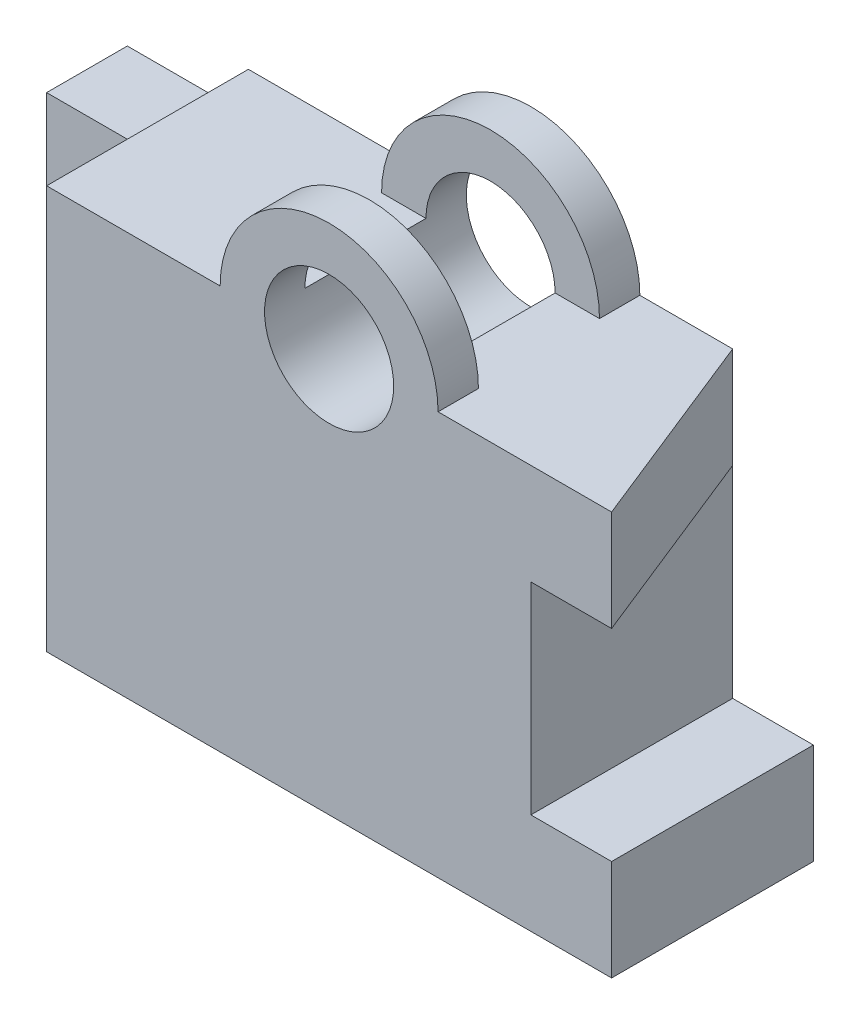
SolidWorks part; units mm, degrees
ref_plane "Спереди" through (0, 0, 0) normal (0, 0, 1) x (1, 0, 0)
ref_plane "Сверху" through (0, 0, 0) normal (0, 1, 0) x (1, 0, 0)
ref_plane "Справа" through (0, 0, 0) normal (1, 0, 0) x (0, 0, -1)
sketch "Эскиз1" plane through (0, 0, 0) normal (0, 0, 1) x (1, 0, 0)
  line L1 (-35, -25) -> (35, -25)
  line L2 (-35, -25) -> (-35, 25)
  line L3 (-35, 25) -> (35, 25)
  line L4 (35, -25) -> (35, 25)
  line L5 (-35, -25) -> (35, 25) construction
  line L6 (-35, 25) -> (35, -25) construction
  line L7 (25, -12.5) -> (35, -12.5)
  line L8 (25, -12.5) -> (25, 12.5)
  line L9 (25, 12.5) -> (35, 12.5)
  line L10 (35, -12.5) -> (35, 12.5)
  line L11 (25, -12.5) -> (35, 12.5) construction
  line L12 (25, 12.5) -> (35, -12.5) construction
  line L13 (-4, -19) -> (4, -19)
  line L14 (-4, -19) -> (-4, -4)
  line L15 (-4, -4) -> (4, -4)
  line L16 (4, -19) -> (4, -4)
  line L17 (-4, -19) -> (4, -4) construction
  line L18 (-4, -4) -> (4, -19) construction
  line L19 (-4, -4) -> (0, -4)
  line L20 (-4, -4) -> (-4, 4)
  line L21 (-4, 4) -> (0, 4)
  line L22 (0, -4) -> (0, 4)
  circle A0 centre (0, 25) radius 8
  point P0 (0, 0)
  point P6 (30, 0)
  point P13 (0, -11.5)
  dimension "D5" = 16
  dimension "D1" = 70
  dimension "D2" = 50
  dimension "D3" = 10
  dimension "D4" = 25
  dimension "D6" = 6
  dimension "D7" = 8
  dimension "D8" = 15
  dimension "D9" = 8
extrude "Бобышка-Вытянуть1" add sketch "Эскиз1" along normal blind 25 contours A0 L3 L2 L1 L4 L7 L8 L9 L22 L15 L16 L13 L14 L20 L21
sketch "Эскиз3" plane through (0, 0, 25) normal (0, 0, 1) x (1, 0, 0)
  circle A0 centre (0, 25) radius 13.5
  circle A1 centre (0, 25) radius 8
  arc A2 (-8, 25) -> (8, 25) centre (0, 25) ccw construction
  dimension "D1" = 27
extrude "Бобышка-Вытянуть2" add sketch "Эскиз3" against normal blind 5
sketch "Эскиз4" plane through (0, 12.5, 0) normal (0, -1, 0) x (1, 0, 0)
  line L0 (35, 25) -> (25, 0)
  line L1 (25, 0) -> (35, 0)
  line L2 (35, 0) -> (35, 25)
extrude "Вырез-Вытянуть1" cut sketch "Эскиз4" against normal through all
sketch "Эскиз5" plane through (0, 0, 25) normal (0, 0, 1) x (1, 0, 0)
  line L0 (-35, 0) -> (25, 0) construction
  line L1 (-35, -25) -> (-35, 25) construction
  line L2 (25, -12.5) -> (25, 12.5) construction
  line L4 (-25, -7) -> (-35, -7)
  line L5 (-25, -7) -> (-25, 7)
  line L6 (-25, 7) -> (-35, 7)
  line L7 (-35, -7) -> (-35, 7)
  line L8 (-25, -7) -> (-35, 7) construction
  line L9 (-25, 7) -> (-35, -7) construction
  point P6 (-30, 0)
  dimension "D1" = 14
  dimension "D2" = 10
extrude "Бобышка-Вытянуть3" add sketch "Эскиз5" along normal blind 11
sketch "Эскиз6" plane through (0, 0, 0) normal (0, 0, -1) x (-1, 0, 0)
  line L0 (25, 7) -> (35, 7) construction
  line L1 (35, 20) -> (50, 20)
  line L2 (35, 20) -> (35, 7)
  line L3 (35, 7) -> (50, 7)
  line L4 (50, 20) -> (50, 7)
  line L5 (35, 7) -> (35, 25) construction
  dimension "D1" = 13
  dimension "D2" = 15
extrude "Бобышка-Вытянуть4" add sketch "Эскиз6" against normal blind 10
sketch "Эскиз7" plane through (0, 0, 36) normal (0, 0, 1) x (1, 0, 0)
  line L4 (-35, 7) -> (-35, -7)
  line L5 (-35, -7) -> (-25, -7)
  line L6 (-25, -7) -> (-25, 7)
  line L7 (-25, 7) -> (-35, 7)
  line L8 (-35, 7) -> (-35, -7)
  line L9 (-35, -7) -> (-25, -7)
  line L10 (-25, -7) -> (-25, 7)
  line L11 (-25, 7) -> (-35, 7)
  dimension "D1" = 0
extrude "Вырез-Вытянуть2" cut sketch "Эскиз7" against normal up to surface (11 mm away) up to face at (0, 3.25, 25)
sketch "Эскиз8" plane through (0, 0, 0) normal (0, 0, -1) x (-1, 0, 0)
  line L0 (50, 7) -> (50, 20) construction
  line L1 (35, 7) -> (20, 7)
  line L2 (35, 7) -> (35, -6)
  line L3 (35, -6) -> (20, -6)
  line L4 (20, 7) -> (20, -6)
  line L5 (35, 7) -> (50, 7) construction
extrude "Бобышка-Вытянуть5" add sketch "Эскиз8" along normal blind 10
sketch "Эскиз9" plane through (0, 7, 0) normal (0, 1, 0) x (1, 0, 0)
  line L4 (-35, 0) -> (-20, 0)
  line L5 (-20, 0) -> (-20, 10)
  line L6 (-20, 10) -> (-35, 10)
  line L7 (-35, 10) -> (-35, 0)
  line L8 (-35, 0) -> (-20, 0)
  line L9 (-20, 0) -> (-20, 10)
  line L10 (-20, 10) -> (-35, 10)
  line L11 (-35, 10) -> (-35, 0)
  dimension "D1" = 0
extrude "Вырез-Вытянуть3" cut sketch "Эскиз9" against normal blind 3
sketch "Эскиз10" plane through (0, 0, 0) normal (0, 0, -1) x (-1, 0, 0)
  line L0 (4, -19) -> (4, 4) construction
  line L1 (4, 4) -> (0, 4) construction
  line L2 (0, -4) -> (0, 4) construction
  line L3 (0, -4) -> (-4, -4) construction
  line L4 (-4, -19) -> (-4, -4) construction
  line L5 (4, -19) -> (-4, -19) construction
  line L6 (4, -19) -> (4, 4)
  line L7 (4, 4) -> (0, 4)
  line L8 (0, -4) -> (0, 4)
  line L9 (0, -4) -> (-4, -4)
  line L10 (-4, -19) -> (-4, -4)
  line L11 (4, -19) -> (-4, -19)
extrude "Бобышка-Вытянуть6" add sketch "Эскиз10" against normal up to surface (25 mm away) up to face at (12, 3.85, 25)
ref_plane "Плоскость1" through (0, 0, 12.5) normal (0, 0, -1) x (-1, 0, 0)
mirror "Зеркальное отражение1" about plane through (0, 0, 12.5) normal (0, 0, -1) of "Бобышка-Вытянуть2"
